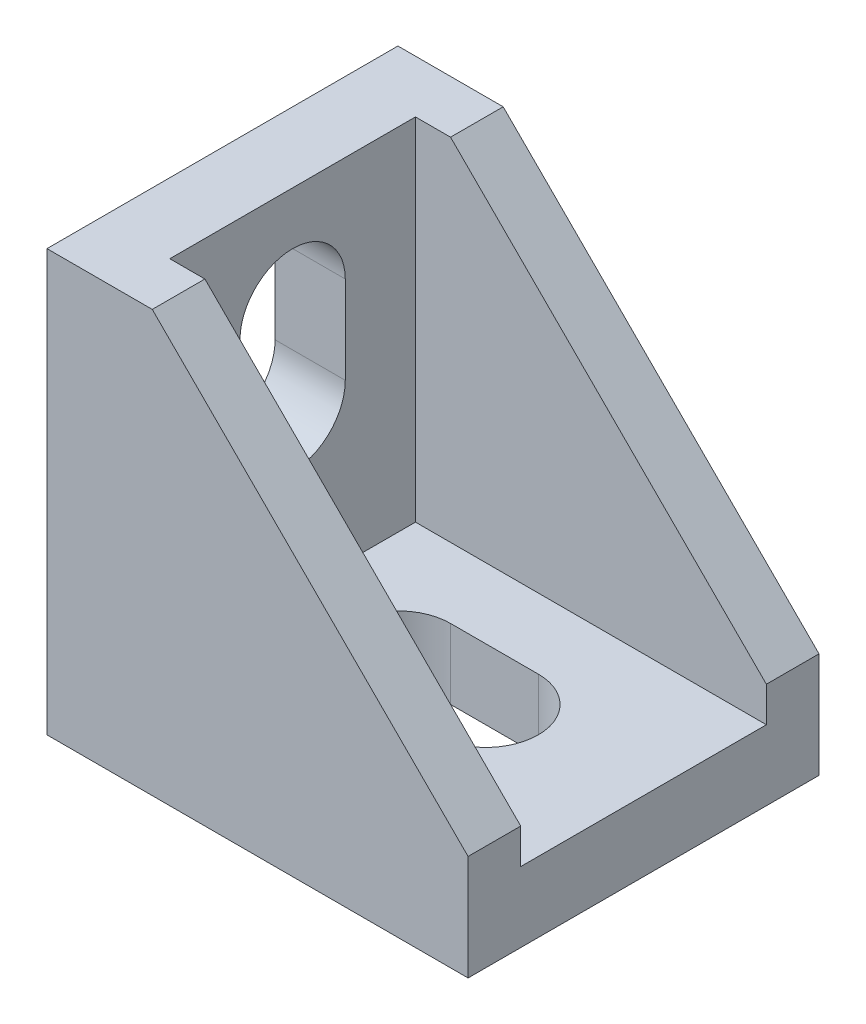
SolidWorks part; units mm, degrees
ref_plane "前视基准面" through (0, 0, 0) normal (0, 0, 1) x (1, 0, 0)
ref_plane "上视基准面" through (0, 0, 0) normal (0, 1, 0) x (1, 0, 0)
ref_plane "右视基准面" through (0, 0, 0) normal (1, 0, 0) x (0, 0, -1)
sketch "草图1" plane through (0, 0, 0) normal (0, 0, 1) x (1, 0, 0)
  line L0 (0, 28) -> (0, 0)
  line L1 (0, 0) -> (28, 0)
  line L2 (28, 0) -> (28, 6)
  line L3 (28, 6) -> (24, 6)
  line L4 (24, 6) -> (6, 24)
  line L5 (6, 24) -> (6, 28)
  line L6 (6, 28) -> (0, 28)
  dimension "D1" = 28
  dimension "D2" = 28
  dimension "D3" = 6
  dimension "D4" = 6
  dimension "D5" = 4
  dimension "D6" = 4
extrude "凸台-拉伸1" add sketch "草图1" along normal blind 20
sketch "草图2" plane through (0, 0, 20) normal (0, 0, 1) x (1, 0, 0)
  line L0 (4, 28) -> (4, 4)
  line L1 (6, 28) -> (0, 28) construction
  line L2 (4, 4) -> (28, 4)
  line L3 (28, 0) -> (28, 6) construction
  line L4 (28, 4) -> (28, 28)
  line L5 (28, 28) -> (4, 28)
  line L6 (0, 28) -> (0, 0) construction
  line L8 (0, 0) -> (28, 0) construction
  dimension "D1" = 4
  dimension "D2" = 4
extrude "切除-拉伸1" cut sketch "草图2" against normal blind 14 from offset 3 offset against normal yes
sketch "草图3" plane through (0, 4, 0) normal (0, 1, 0) x (1, 0, 0)
  line L0 (10, -10) -> (15, -10) construction
  line L1 (28, -3) -> (28, -17) construction
  line L2 (10, -13) -> (15, -13)
  line L3 (10, -7) -> (15, -7)
  arc A0 (10, -13) -> (10, -7) centre (10, -10) cw
  arc A1 (15, -13) -> (15, -7) centre (15, -10) ccw
  dimension "D1" = 13
  dimension "D2" = 5
  dimension "D3" = 3
  dimension "D4" = 3
extrude "切除-拉伸2" cut sketch "草图3" against normal blind 12
sketch "草图4" plane through (4, 0, 0) normal (1, 0, 0) x (0, 0, -1)
  line L0 (-10, 18) -> (-10, 13) construction
  line L1 (-20, 0) -> (0, 0) construction
  line L2 (-13, 18) -> (-13, 13)
  line L3 (-7, 18) -> (-7, 13)
  arc A0 (-13, 18) -> (-7, 18) centre (-10, 18) cw
  arc A1 (-13, 13) -> (-7, 13) centre (-10, 13) ccw
  dimension "D1" = 13
  dimension "D2" = 5
  dimension "D3" = 3
  dimension "D4" = 3
extrude "切除-拉伸3" cut sketch "草图4" against normal blind 12
sketch "草图5" plane through (0, 0, 0) normal (0, 0, -1) x (-1, 0, 0)
  line L1 (0, 28) -> (-6, 28)
  line L2 (0, 28) -> (0, 24)
  line L3 (0, 24) -> (-6, 24)
  line L4 (-6, 28) -> (-6, 24)
  line L5 (-24, 6) -> (-28, 6)
  line L6 (-24, 6) -> (-24, 0)
  line L7 (-24, 0) -> (-28, 0)
  line L8 (-28, 6) -> (-28, 0)
extrude "切除-拉伸4" cut sketch "草图5" against normal blind 30
